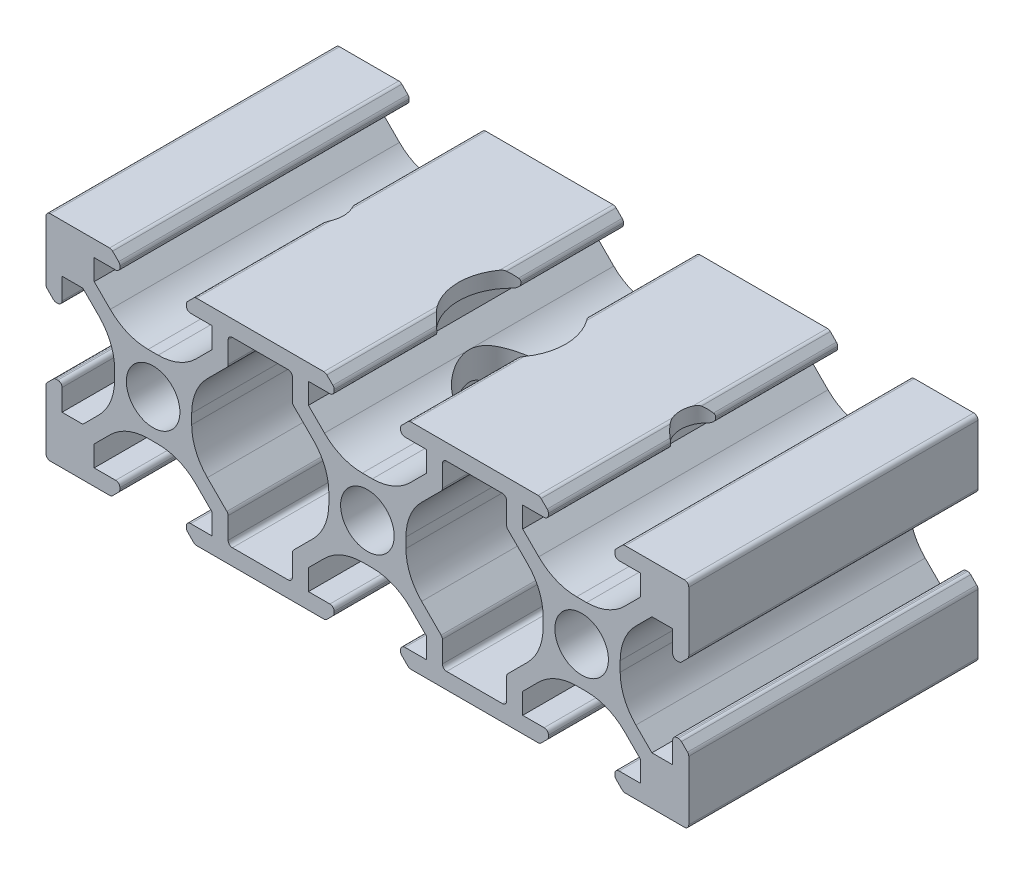
SolidWorks part; units mm, degrees
material "6063-O"
ref_plane "Plano frontal" through (0, 0, 0) normal (0, 0, 1) x (1, 0, 0)
ref_plane "Plano superior" through (0, 0, 0) normal (0, 1, 0) x (1, 0, 0)
ref_plane "Plano direito" through (0, 0, 0) normal (1, 0, 0) x (0, 0, -1)
sketch "Esboço1" plane through (0, 0, 0) normal (0, 0, 1) x (1, 0, 0)
  line L0 (-9.0343, 3.1) -> (-8.9, 3.1)
  line L3 (-10, 10) -> (-4.0657, 10)
  line L5 (-10, -10) -> (10, 10) construction
  line L6 (-10, 10) -> (10, -10) construction
  line L7 (-8.5, 3.5) -> (-8.5, 5.5)
  line L8 (-10, 0) -> (10, 0) construction
  line L9 (0, 10) -> (0, -10) construction
  line L12 (-8.5, 5.5) -> (-6.5607, 5.5)
  line L15 (-6.5607, 5.5) -> (-5.0645, 4.0038)
  line L16 (-3.6, 0.4683) -> (-3.6, 0)
  line L17 (-0.4683, 3.6) -> (0, 3.6)
  line L18 (-5.5, 6.5607) -> (-4.0038, 5.0645)
  line L21 (-5.5, 8.5) -> (-5.5, 6.5607)
  line L24 (-3.5, 8.5) -> (-5.5, 8.5)
  line L25 (-3.1, 9.0343) -> (-3.1, 8.9)
  line L44 (-10, 4.0657) -> (-10, 10)
  line L45 (-9.8828, 3.7828) -> (-9.3172, 3.2172)
  line L46 (-3.7828, 9.8828) -> (-3.2172, 9.3172)
  line L47 (-3.6, 0) -> (-2.5, 0)
  line L48 (0, 3.6) -> (0, 2.5)
  arc A0 (-3.5, 8.5) -> (-3.1, 8.9) centre (-3.5, 8.9) ccw
  arc A1 (-3.7828, 9.8828) -> (-4.0657, 10) centre (-4.0657, 9.6) ccw
  arc A2 (-10, 4.0657) -> (-9.8828, 3.7828) centre (-9.6, 4.0657) ccw
  arc A3 (-8.5, 3.5) -> (-8.9, 3.1) centre (-8.9, 3.5) cw
  arc A4 (-3.2172, 9.3172) -> (-3.1, 9.0343) centre (-3.5, 9.0343) cw
  arc A5 (-9.3172, 3.2172) -> (-9.0343, 3.1) centre (-9.0343, 3.5) ccw
  arc A6 (-3.6, 0.4683) -> (-5.0645, 4.0038) centre (-8.6, 0.4683) ccw
  arc A7 (-4.0038, 5.0645) -> (-0.4683, 3.6) centre (-0.4683, 8.6) ccw
  circle A8 centre (0, 0) radius 2.5
  point P6 (-10, 3.1)
  point P28 (-3.1, 8.5)
  point P31 (-3.1, 10)
  point P33 (-3.9, 10)
  point P36 (-10, 3.9)
  point P39 (-8.5, 3.1)
  point P42 (-3.1, 9.2)
  point P45 (-9.2, 3.1)
  point P48 (-3.6, 2.5393)
  point P51 (-2.5393, 3.6)
  dimension "D5" = 10
  dimension "D9" = 0.4
  dimension "D10" = 0.4
  dimension "D11" = 5
  dimension "D12" = 5
  dimension "D13" = 5
  dimension "D1" = 6.9
  dimension "D2" = 1.5
  dimension "D3" = 3.6
  dimension "D4" = 1.5
  dimension "D6" = 2.4
  dimension "D7" = 3.6
  dimension "D8" = 45
extrude "Ressalto-extrusão1" add sketch "Esboço1" along normal blind 27
sketch "Esboço3" plane through (0, 0, 0) normal (1, 0, 0) x (0, 0, -1)
  line L0 (0, 0) -> (-27, 0) construction
  line L1 (-27, 2.5) -> (-27, 0) construction
  point P3 (0, 0)
pattern_circular "PadrãoCircular1" count 4 over 360 about axis through (0, 0, 0) along (0, 0, 1) of "Ressalto-extrusão1"
pattern_linear "Padrão linear1" count 3 spacing 20 along (1, 0, 0) of "Ressalto-extrusão1", "PadrãoCircular1"
sketch "Esboço4" plane through (0, 0, 0) normal (0, 0, -1) x (-1, 0, 0)
  line L0 (-13.4393, 5.5) -> (-13, 5.9393)
  line L1 (-13, 8.5) -> (-13, 5.9393)
  line L2 (-10, 10) -> (-10, -10) construction
  line L3 (-4.0657, 10) -> (-15.9343, 10) construction
  line L4 (-15.9343, -10) -> (-4.0657, -10) construction
  line L5 (-11.5, 5.5) -> (-13.4393, 5.5) construction
  line L6 (-14.5, 8.5) -> (-14.5, 6.5607) construction
  line L7 (-7, 8.5) -> (-7, 5.9393)
  line L8 (-6.5607, 5.5) -> (-7, 5.9393)
  line L9 (-13, 8.5) -> (-7, 8.5)
  line L10 (-20, 0) -> (0, 0) construction
  line L11 (-13, -8.5) -> (-7, -8.5)
  line L12 (-6.5607, -5.5) -> (-7, -5.9393)
  line L13 (-7, -8.5) -> (-7, -5.9393)
  line L14 (-13, -8.5) -> (-13, -5.9393)
  line L15 (-13.4393, -5.5) -> (-13, -5.9393)
  line L16 (-13.4393, 5.5) -> (-13.4393, -5.5)
  line L17 (-6.5607, -5.5) -> (-6.5607, 5.5)
  line L31 (-40, 0) -> (-20, 0) construction
  line L32 (-33.4393, 5.5) -> (-33, 5.9393) [skipped]
  line L33 (-33, 8.5) -> (-33, 5.9393) [skipped]
  line L34 (-27, 8.5) -> (-27, 5.9393) [skipped]
  line L35 (-26.5607, 5.5) -> (-27, 5.9393) [skipped]
  line L36 (-33, 8.5) -> (-27, 8.5) [skipped]
  line L37 (-33, -8.5) -> (-27, -8.5) [skipped]
  line L38 (-26.5607, -5.5) -> (-27, -5.9393) [skipped]
  line L39 (-27, -8.5) -> (-27, -5.9393) [skipped]
  line L40 (-33, -8.5) -> (-33, -5.9393) [skipped]
  line L41 (-33.4393, -5.5) -> (-33, -5.9393) [skipped]
  line L42 (-33.4393, 5.5) -> (-33.4393, -5.5) [skipped]
  line L43 (-26.5607, -5.5) -> (-26.5607, 5.5) [skipped]
  line L44 (-30, 10) -> (-30, -10) construction
  dimension "D1" = 45
  dimension "D2" = 1.5
  dimension "D3" = 1.5
  dimension "D4" = 2
extrude "Corte-extrusão1" cut sketch "Esboço4" against normal through all
pattern_linear "Padrão linear2" count 2 spacing 20 along (1, 0, 0) of "Corte-extrusão1"
fillet "Filete1" radius 0.4 16 edges at (13, -5.9393, 13.5) (13, -8.5, 13.5) (7, -8.5, 13.5) (7, -5.9393, 13.5) (7, 8.5, 13.5) (7, 5.9393, 13.5) (13, 8.5, 13.5) (13, 5.9393, 13.5) (27, -8.5, 13.5) (27, -5.9393, 13.5) (27, 8.5, 13.5) (27, 5.9393, 13.5) (33, 8.5, 13.5) (33, -8.5, 13.5) (33, -5.9393, 13.5) (33, 5.9393, 13.5)
fillet "Filete2" radius 0.4 4 edges at (-10, 10, 13.5) (50, -10, 13.5) (50, 10, 13.5) (-10, -10, 13.5)
sketch "Sketch1" plane through (0, 10, 0) normal (0, 1, 0) x (1, 0, 0)
  line L0 (49.6, -13.5) -> (-9.6, -13.5) construction
  line L1 (49.6, -27) -> (49.6, 0) construction
  line L2 (-9.6, 0) -> (-9.6, -27) construction
  line L3 (20, -13.5) -> (20, -30.4194) construction
  circle A0 centre (20, -13.5) radius 5
  circle A1 centre (38.25, -13.5) radius 2.5
  circle A2 centre (1.75, -13.5) radius 2.5
  dimension "D1" = 10
  dimension "D2" = 5
  dimension "D3" = 36.5
extrude "Cut-Extrude1" cut sketch "Sketch1" against normal blind 3
sketch "Sketch2" plane through (0, 10, 0) normal (0, 1, 0) x (1, 0, 0)
  circle A0 centre (20, -13.5) radius 4
  dimension "D1" = 8
extrude "Cut-Extrude2" cut sketch "Sketch2" against normal through all
